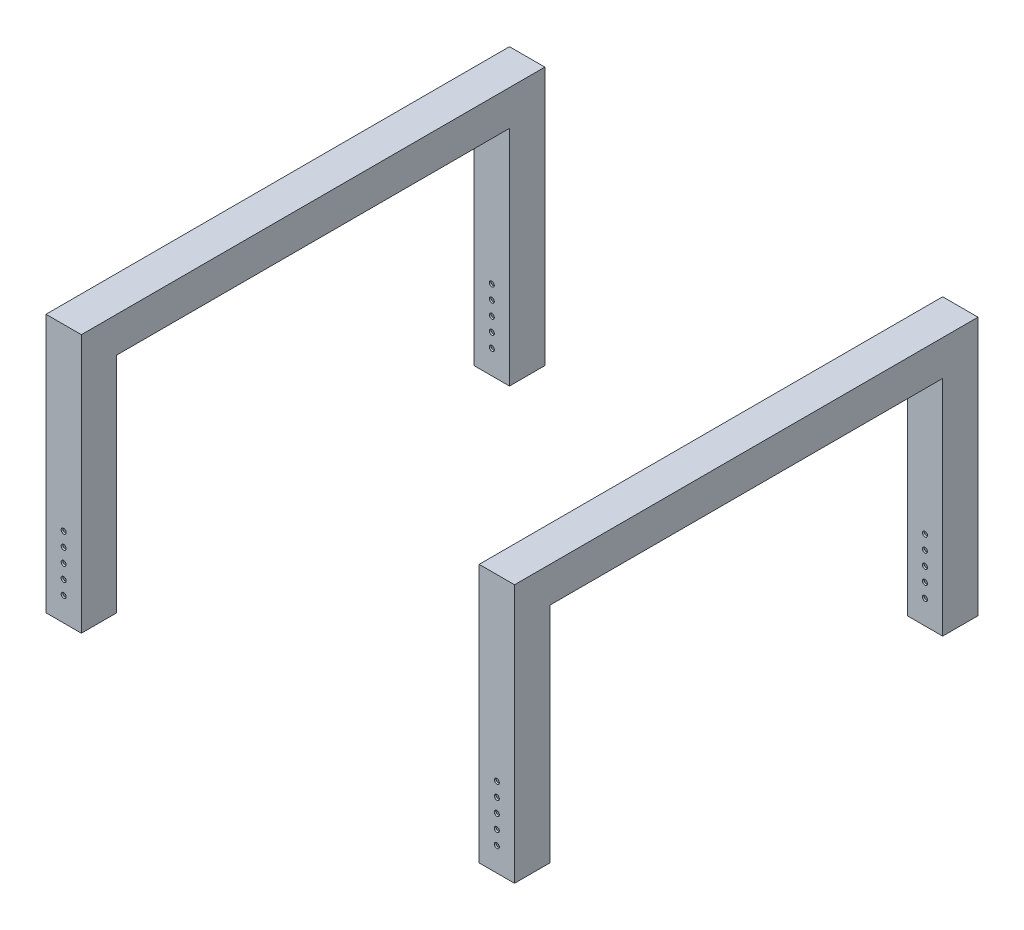
SolidWorks part; units mm, degrees
ref_plane "Alzado" through (0, 0, 0) normal (0, 0, 1) x (1, 0, 0)
ref_plane "Planta" through (0, 0, 0) normal (0, 1, 0) x (1, 0, 0)
ref_plane "Vista lateral" through (0, 0, 0) normal (1, 0, 0) x (0, 0, -1)
sketch "Croquis1" plane through (0, 0, 0) normal (0, 1, 0) x (1, 0, 0)
  line L0 (88.9, 0) -> (1088.9, 0) construction
  line L1 (0, 0) -> (88.9, 0)
  line L2 (0, 0) -> (0, -88.9)
  line L3 (0, -88.9) -> (88.9, -88.9)
  line L4 (88.9, 0) -> (88.9, -88.9)
  line L5 (0, -88.9) -> (0, -582.55) construction
  line L6 (1088.9, 0) -> (1177.8, 0)
  line L7 (1088.9, 0) -> (1088.9, -88.9)
  line L8 (1088.9, -88.9) -> (1177.8, -88.9)
  line L9 (1177.8, 0) -> (1177.8, -88.9)
  line L10 (0, -582.55) -> (329.6526, -582.55) construction
  line L11 (88.9, -1165.1) -> (1088.9, -1165.1) construction
  line L12 (1177.8, -1165.1) -> (1177.8, -1076.2)
  line L13 (1088.9, -1076.2) -> (1177.8, -1076.2)
  line L14 (1088.9, -1165.1) -> (1088.9, -1076.2)
  line L15 (1088.9, -1165.1) -> (1177.8, -1165.1)
  line L16 (88.9, -1165.1) -> (88.9, -1076.2)
  line L17 (0, -1076.2) -> (88.9, -1076.2)
  line L18 (0, -1165.1) -> (0, -1076.2)
  line L19 (0, -1165.1) -> (88.9, -1165.1)
  point P19 (1133.35, 0)
  point P20 (44.45, 0)
  point P21 (0, -1120.65)
  point P22 (0, -44.45)
  dimension "D1" = 88.9
  dimension "D2" = 88.9
  dimension "D3" = 88.9
  dimension "D4" = 88.9
  dimension "D5" = 1000
  dimension "D6" = 493.65
  dimension "D7" = 1088.9
  dimension "D8" = 1076.2
extrude "Saliente-Extruir1" add sketch "Croquis1" along normal blind 650
sketch "Croquis7" plane through (0, 0, 0) normal (0, -1, 0) x (1, 0, 0)
  line L0 (1133.35, 0) -> (1133.35, 88.9) construction
  line L1 (1177.8, 0) -> (1088.9, 0) construction
  line L2 (1088.9, 88.9) -> (1177.8, 88.9) construction
  line L3 (44.45, 0) -> (44.45, 88.9) construction
  line L4 (1173.35, 84.45) -> (1093.35, 84.45)
  line L5 (1173.35, 84.45) -> (1173.35, 4.45)
  line L6 (1173.35, 4.45) -> (1093.35, 4.45)
  line L7 (1093.35, 84.45) -> (1093.35, 4.45)
  line L8 (1173.35, 84.45) -> (1093.35, 4.45) construction
  line L9 (1173.35, 4.45) -> (1093.35, 84.45) construction
  line L10 (88.9, 0) -> (0, 0) construction
  line L11 (0, 88.9) -> (88.9, 88.9) construction
  line L13 (84.45, 84.45) -> (4.45, 84.45)
  line L14 (84.45, 84.45) -> (84.45, 4.45)
  line L15 (84.45, 4.45) -> (4.45, 4.45)
  line L16 (4.45, 84.45) -> (4.45, 4.45)
  line L17 (84.45, 84.45) -> (4.45, 4.45) construction
  line L18 (84.45, 4.45) -> (4.45, 84.45) construction
  point P6 (1133.35, 44.45)
  point P17 (44.45, 44.45)
  point P28 (1333.35, 1133.35)
  point P39 (44.45, 1133.35)
  dimension "D1" = 80
  dimension "D2" = 80
  dimension "D3" = 80
  dimension "D4" = 80
extrude "Cortar-Extruir5" cut sketch "Croquis7" against normal blind 550
sketch "Croquis8" plane through (0, 0, 0) normal (0, -1, 0) x (1, 0, 0)
  line L0 (1133.35, 1076.2) -> (1133.35, 1165.1) construction
  line L1 (1177.8, 1076.2) -> (1088.9, 1076.2) construction
  line L2 (1088.9, 1165.1) -> (1177.8, 1165.1) construction
  line L3 (44.45, 1076.2) -> (44.45, 1165.1) construction
  line L4 (1173.35, 1160.65) -> (1093.35, 1160.65)
  line L5 (1173.35, 1160.65) -> (1173.35, 1080.65)
  line L6 (1173.35, 1080.65) -> (1093.35, 1080.65)
  line L7 (1093.35, 1160.65) -> (1093.35, 1080.65)
  line L8 (1173.35, 1160.65) -> (1093.35, 1080.65) construction
  line L9 (1173.35, 1080.65) -> (1093.35, 1160.65) construction
  line L10 (88.9, 1076.2) -> (0, 1076.2) construction
  line L11 (0, 1165.1) -> (88.9, 1165.1) construction
  line L13 (84.45, 1160.65) -> (4.45, 1160.65)
  line L14 (84.45, 1160.65) -> (84.45, 1080.65)
  line L15 (84.45, 1080.65) -> (4.45, 1080.65)
  line L16 (4.45, 1160.65) -> (4.45, 1080.65)
  line L17 (84.45, 1160.65) -> (4.45, 1080.65) construction
  line L18 (84.45, 1080.65) -> (4.45, 1160.65) construction
  point P6 (1133.35, 1120.65)
  point P17 (44.45, 1120.65)
  dimension "D1" = 80
  dimension "D2" = 80
  dimension "D3" = 80
  dimension "D4" = 80
extrude "Cortar-Extruir6" cut sketch "Croquis8" against normal blind 550
sketch "Croquis9" plane through (0, 0, 1165.1) normal (0, 0, 1) x (1, 0, 0)
  line L0 (44.45, 0) -> (44.45, 60) construction
  line L1 (0, 0) -> (88.9, 0) construction
  line L2 (44.45, 60) -> (44.45, 95) construction
  line L3 (44.45, 95) -> (44.45, 130) construction
  line L4 (44.45, 130) -> (44.45, 165) construction
  line L5 (44.45, 165) -> (44.45, 200) construction
  circle A0 centre (44.45, 60) radius 6.35
  circle A1 centre (44.45, 95) radius 6.35
  circle A2 centre (44.45, 130) radius 6.35
  circle A3 centre (44.45, 165) radius 6.35
  circle A4 centre (44.45, 200) radius 6.35
  dimension "D2" = 12.7
  dimension "D3" = 12.7
  dimension "D4" = 12.7
  dimension "D9" = 12.7
  dimension "D10" = 12.7
  dimension "D1" = 60
  dimension "D5" = 35
  dimension "D6" = 35
  dimension "D7" = 35
  dimension "D8" = 35
extrude "Cortar-Extruir7" cut sketch "Croquis9" against normal blind 1200
sketch "Croquis10" plane through (0, 0, 1165.1) normal (0, 0, 1) x (1, 0, 0)
  line L0 (1133.35, 0) -> (1133.35, 60) construction
  line L1 (1088.9, 0) -> (1177.8, 0) construction
  line L2 (1133.35, 60) -> (1133.35, 95) construction
  line L3 (1133.35, 95) -> (1133.35, 130) construction
  line L4 (1133.35, 130) -> (1133.35, 165) construction
  line L5 (1133.35, 165) -> (1133.35, 200) construction
  circle A0 centre (1133.35, 60) radius 6.35
  circle A1 centre (1133.35, 95) radius 6.35
  circle A2 centre (1133.35, 130) radius 6.35
  circle A3 centre (1133.35, 165) radius 6.35
  circle A4 centre (1133.35, 200) radius 6.35
  dimension "D6" = 12.7
  dimension "D7" = 12.7
  dimension "D8" = 12.7
  dimension "D9" = 12.7
  dimension "D10" = 12.7
  dimension "D1" = 60
  dimension "D2" = 35
  dimension "D3" = 35
  dimension "D4" = 35
  dimension "D5" = 35
extrude "Cortar-Extruir8" cut sketch "Croquis10" against normal blind 1200
sketch "Croquis12" plane through (0, 0, 88.9) normal (0, 0, 1) x (1, 0, 0)
  line L0 (88.9, 650) -> (88.9, 0) construction
  line L1 (0, 650) -> (88.9, 650)
  line L2 (0, 650) -> (0, 561.1)
  line L3 (0, 561.1) -> (88.9, 561.1)
  line L4 (88.9, 650) -> (88.9, 561.1)
  dimension "D1" = 88.9
extrude "Saliente-Extruir3" add sketch "Croquis12" along normal up to surface (987.3 mm away) up to face at (50.8, 60, 1076.2)
sketch "Croquis13" plane through (0, 0, 88.9) normal (0, 0, 1) x (1, 0, 0)
  line L0 (1177.8, 650) -> (1177.8, 0) construction
  line L1 (1088.9, 650) -> (1177.8, 650)
  line L2 (1088.9, 650) -> (1088.9, 561.1)
  line L3 (1088.9, 561.1) -> (1177.8, 561.1)
  line L4 (1177.8, 650) -> (1177.8, 561.1)
  dimension "D1" = 88.9
extrude "Saliente-Extruir4" add sketch "Croquis13" along normal up to surface (987.3 mm away) up to face at (1139.7, 60, 1076.2)
